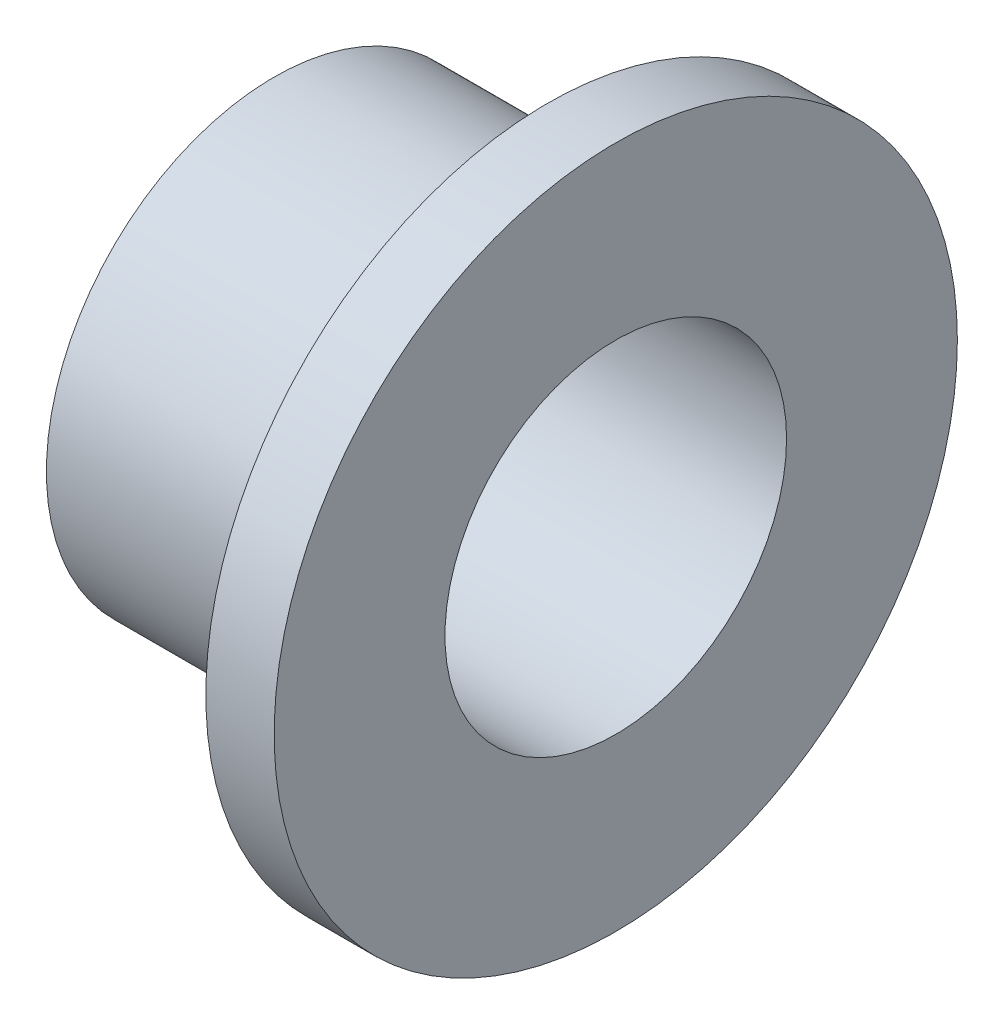
SolidWorks part; units mm, degrees
ref_plane "Alzado" through (0, 0, 0) normal (1, 0, 0) x (0, 1, 0)
ref_plane "Planta" through (0, 0, 0) normal (0, 0, 1) x (0, 1, 0)
ref_plane "Vista lateral" through (0, 0, 0) normal (0, 1, 0) x (-1, 0, 0)
sketch "Croquis1" plane through (0, 0, 0) normal (0, 1, 0) x (-1, 0, 0)
  line L0 (0, 6) -> (0, 3)
  line L1 (0, 3) -> (6, 3)
  line L2 (6, 3) -> (6, 4)
  line L3 (6, 4) -> (1.2, 4)
  line L4 (1.2, 4) -> (1.2, 6)
  line L5 (1.2, 6) -> (0, 6)
  line L6 (0, 0) -> (6, 0) construction
  dimension "D1" = 6
  dimension "D2" = 12
  dimension "D3" = 1.2
  dimension "D4" = 6
  dimension "D5" = 8
revolve "Revolución1" add sketch "Croquis1" angle 360 about L6
